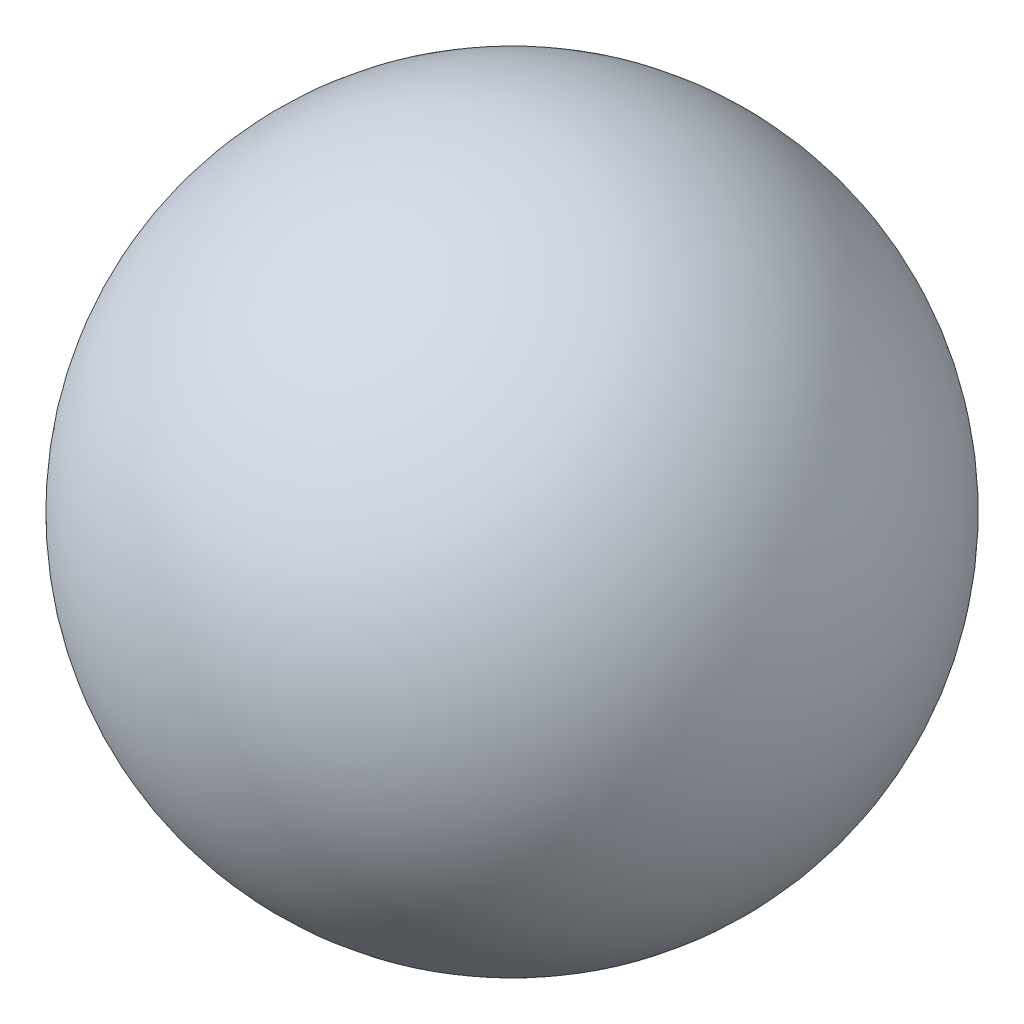
SolidWorks part; units mm, degrees
material "Ti-10V-2Fe-3Al Solution Treated Bar (SS)"
ref_plane "Front Plane" through (0, 0, 0) normal (0, 0, 1) x (1, 0, 0)
ref_plane "Top Plane" through (0, 0, 0) normal (0, 1, 0) x (1, 0, 0)
ref_plane "Right Plane" through (0, 0, 0) normal (1, 0, 0) x (0, 0, -1)
sketch "Sketch1" plane through (0, 0, 0) normal (0, 0, 1) x (1, 0, 0)
  line L0 (0, 403) -> (0, 400)
  line L1 (0, -400) -> (0, -403)
  arc A0 (0, 403) -> (0, -403) centre (0, 0) ccw
  arc A1 (0, 400) -> (0, -400) centre (0, 0) ccw
revolve "Revolve1" add sketch "Sketch1" angle 360 about L0
